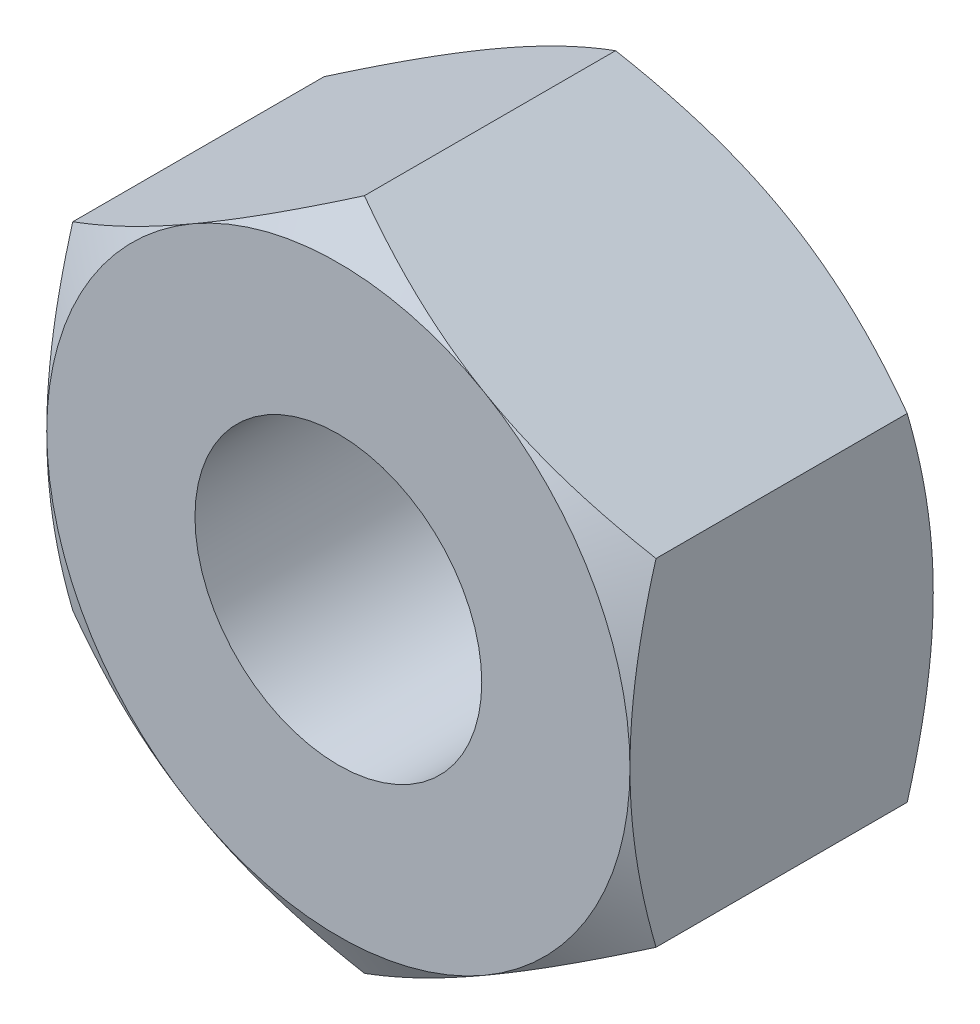
SolidWorks part; units mm, degrees
ref_plane "基准面1" through (0, 0, 0) normal (0, 0, 1) x (1, 0, 0)
ref_plane "基准面2" through (0, 0, 0) normal (0, 1, 0) x (1, 0, 0)
ref_plane "基准面3" through (0, 0, 0) normal (1, 0, 0) x (0, 0, -1)
sketch "尺寸草图" plane through (0, 0, 0) normal (0, 0, 1) x (1, 0, 0)
  line L0 (0, 0) -> (11, 0) construction
  line L1 (0, 0) -> (22, 0) construction
  line L2 (11, 0) -> (19.9, 0) construction
  line L3 (-5.7143, 0) -> (0, 0) construction
  point P3 (6, 0)
  point P4 (1, 0)
  point P5 (11, 0)
  point P6 (5.2, 0)
  point P8 (10, 0)
  dimension "D1" = 5.7143
  dimension "D" = 6
  dimension "P" = 1
  dimension "e(最小)" = 11
  dimension "m(最大)" = 5.2
  dimension "s(公称)" = 10
  dimension "dw(最小)" = 8.9
sketch "草图1" plane through (0, 0, 0) normal (0, 0, 1) x (1, 0, 0)
  line L0 (-5, 0) -> (5, 0) construction
  line L1 (0, 5.7735) -> (0, -5.7735) construction
  line L3 (0, 5.7735) -> (-5, 2.8868)
  line L4 (-5, 2.8868) -> (-5, -2.8868)
  line L5 (-5, -2.8868) -> (0, -5.7735)
  line L6 (0, -5.7735) -> (5, -2.8868)
  line L7 (5, -2.8868) -> (5, 2.8868)
  line L8 (5, 2.8868) -> (0, 5.7735)
  circle A0 centre (0, 0) radius 5 construction
  circle A1 centre (0, 0) radius 2.4587
  point P2 (0, 5.2265)
  dimension "D1" = 11
  dimension "D" = 4.9175
  dimension "D2" = 10
extrude "基体-拉伸" add sketch "草图1" along normal blind 5.2
cosmetic thread "装饰螺纹线1" parameters "D2"=6
sketch "草图2" plane through (0, 0, 0) normal (0, 0, -1) x (-1, 0, 0)
  circle A0 centre (0, 0) radius 5
  circle A1 centre (0, 0) radius 2.4587 construction
  dimension "s" = 10
extrude "切除-拉伸1" cut sketch "草图2" against normal through all draft 60 flip side to cut
sketch "草图3" plane through (0, 0, 5.2) normal (0, 0, 1) x (1, 0, 0)
  circle A0 centre (0, 0) radius 5
  dimension "D1" = 10
extrude "切除-拉伸2" cut sketch "草图3" against normal through all draft 60 flip side to cut
